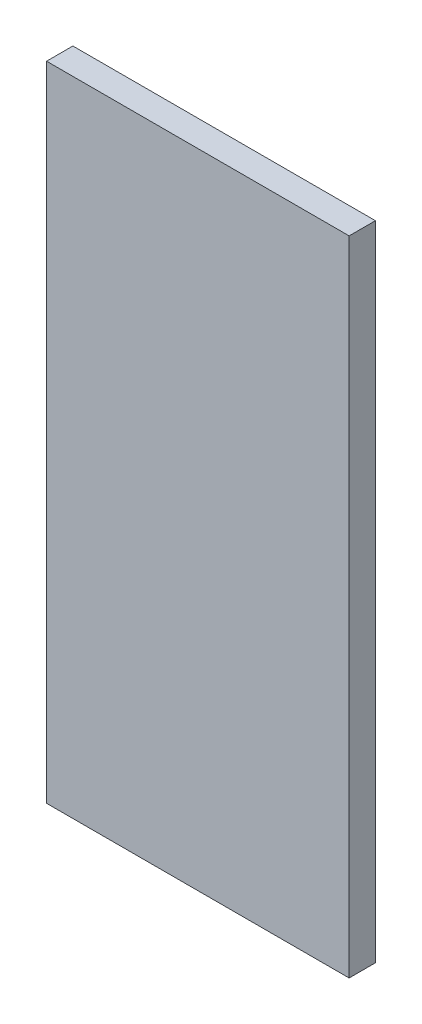
SolidWorks part; units mm, degrees
ref_plane "前视基准面" through (0, 0, 0) normal (0, 0, 1) x (1, 0, 0)
ref_plane "上视基准面" through (0, 0, 0) normal (0, 1, 0) x (1, 0, 0)
ref_plane "右视基准面" through (0, 0, 0) normal (1, 0, 0) x (0, 0, -1)
other "Configuration Table"
sketch "草图1" plane through (0, 0, 0) normal (0, 0, 1) x (1, 0, 0)
  line L1 (-80.5, 171) -> (80.5, 171)
  line L2 (-80.5, 171) -> (-80.5, -171)
  line L3 (-80.5, -171) -> (80.5, -171)
  line L4 (80.5, 171) -> (80.5, -171)
  line L5 (-80.5, 171) -> (80.5, -171) construction
  line L6 (-80.5, -171) -> (80.5, 171) construction
  point P0 (0, 0)
  dimension "D1" = 161
  dimension "D2" = 342
extrude "凸台-拉伸1" add sketch "草图1" along normal blind 14
